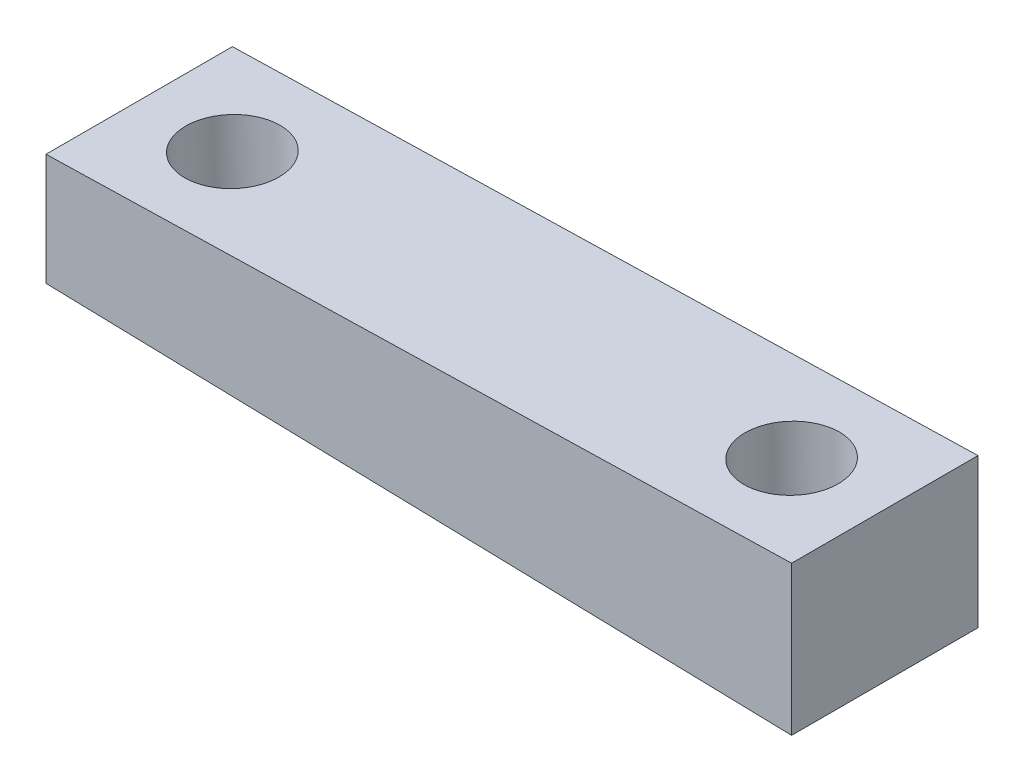
SolidWorks part; units mm, degrees
ref_plane "Plan de face" through (0, 0, 0) normal (0, 0, 1) x (1, 0, 0)
ref_plane "Plan de dessus" through (0, 0, 0) normal (0, 1, 0) x (1, 0, 0)
ref_plane "Plan de droite" through (0, 0, 0) normal (1, 0, 0) x (0, 0, -1)
sketch "Esquisse1" plane through (0, 0, 0) normal (0, 0, 1) x (1, 0, 0)
  line L0 (0, 0) -> (40, 1)
  line L1 (40, 1) -> (40, -7)
  line L2 (40, -7) -> (0, -6)
  line L3 (0, -6) -> (0, 0)
  dimension "D1" = 6
  dimension "D2" = 8
  dimension "D3" = 40
extrude "Boss.-Extru.1" add sketch "Esquisse1" along normal blind 10
sketch "Esquisse2" plane through (0, 0, 0) normal (-0.025, 0.9997, 0) x (0.9997, 0.025, 0)
  line L0 (0, -10) -> (0, 0) construction
  line L2 (40.0125, -10) -> (40.0125, 0) construction
  line L3 (5, -5) -> (0, -5) construction
  circle A0 centre (5, -5) radius 2.5
  circle A1 centre (35.0125, -5) radius 2.5
  dimension "D1" = 5
  dimension "D2" = 5
  dimension "D3" = 5
  dimension "D4" = 5
extrude "Enlèv. mat.-Extru.1" cut sketch "Esquisse2" against normal through all
